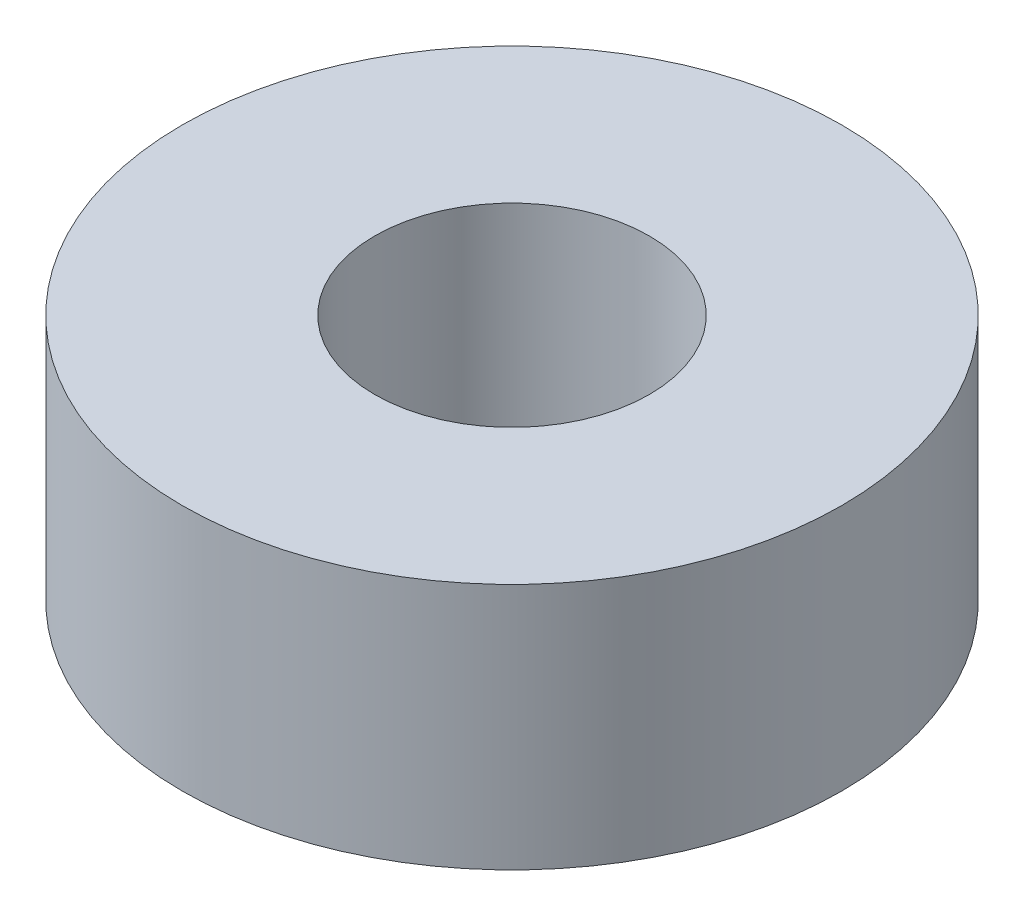
SolidWorks part; units mm, degrees
ref_plane "Front Plane" through (0, 0, 0) normal (0, 0, 1) x (1, 0, 0)
ref_plane "Top Plane" through (0, 0, 0) normal (0, 1, 0) x (1, 0, 0)
ref_plane "Right Plane" through (0, 0, 0) normal (1, 0, 0) x (0, 0, -1)
sketch "Sketch1" plane through (0, 0, 0) normal (0, 1, 0) x (1, 0, 0)
  circle A0 centre (0, 0) radius 12
  circle A1 centre (0, 0) radius 5
  dimension "D1" = 24
  dimension "D2" = 10
extrude "Boss-Extrude1" add sketch "Sketch1" along normal blind 9
